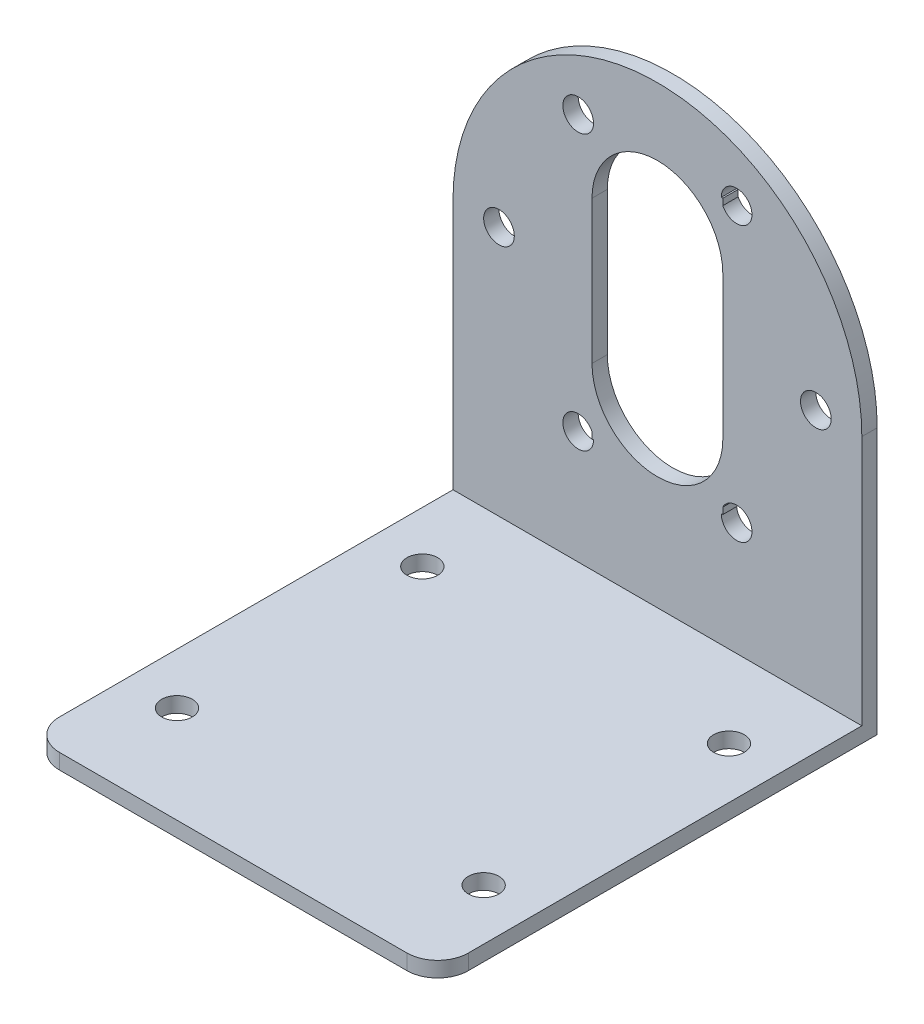
SolidWorks part; units mm, degrees
ref_plane "Alzado" through (0, 0, 0) normal (0, 0, 1) x (1, 0, 0)
ref_plane "Planta" through (0, 0, 0) normal (0, 1, 0) x (1, 0, 0)
ref_plane "Vista lateral" through (0, 0, 0) normal (1, 0, 0) x (0, 0, -1)
sketch "Croquis1" plane through (0, 0, 0) normal (0, 0, 1) x (1, 0, 0)
  line L1 (0, 0) -> (40, 0)
  line L2 (0, 0) -> (0, 26)
  line L4 (40, 0) -> (40, 26)
  arc A0 (40, 26) -> (0, 26) centre (20, 26) ccw
  dimension "D3" = 40
  dimension "D5" = 20
  dimension "D1" = 40
extrude "Saliente-Extruir1" add sketch "Croquis1" along normal blind 1.5
sketch "Croquis2" plane through (0, 0, 1.5) normal (0, 0, 1) x (1, 0, 0)
  line L0 (40, 0) -> (40, 26) construction
  line L1 (0, 0) -> (40, 0)
  line L2 (0, 0) -> (0, 1.5)
  line L3 (0, 1.5) -> (40, 1.5)
  line L4 (40, 0) -> (40, 1.5)
  dimension "D1" = 1.5
extrude "Saliente-Extruir2" add sketch "Croquis2" along normal blind 41.5
sketch "Croquis3" plane through (0, 1.5, 0) normal (0, 1, 0) x (1, 0, 0)
  line L0 (0, -43) -> (0, -1.5) construction
  line L1 (40, -43) -> (0, -43) construction
  circle A0 centre (5, -33.5) radius 1.5
  circle A1 centre (5, -9.5) radius 1.5
  circle A2 centre (35, -9.5) radius 1.5
  circle A3 centre (35, -33.5) radius 1.5
  dimension "D3" = 3
  dimension "D4" = 3
  dimension "D8" = 30
  dimension "D1" = 5
  dimension "D2" = 9.5
  dimension "D5" = 5
  dimension "D6" = 24
  dimension "D7" = 30
  dimension "D9" = 9.5
  dimension "D10" = 24
extrude "Cortar-Extruir1" cut sketch "Croquis3" against normal blind 41.5
sketch "Croquis4" plane through (0, 0, 1.5) normal (0, 0, 1) x (1, 0, 0)
  line L0 (20, 26) -> (24.305, 26) construction
  line L1 (13.6, 33) -> (13.6, 19)
  line L2 (13.6, 39.4) -> (13.7498, 39.4)
  line L3 (13.6, 39.4) -> (13.6, 38.7696)
  line L4 (13.6, 12.6) -> (13.7498, 12.6)
  line L5 (26.4, 39.4) -> (26.4, 38.7696)
  line L6 (26.2502, 39.4) -> (26.4, 39.4)
  line L7 (26.4, 33) -> (26.4, 19)
  line L8 (26.2502, 12.6) -> (26.4, 12.6)
  line L9 (13.6, 13.2304) -> (13.6, 12.6)
  line L10 (26.4, 13.2304) -> (26.4, 12.6)
  circle A0 centre (20, 26) radius 15.5 construction
  circle A1 centre (4.5, 26) radius 1.5
  circle A2 centre (12.25, 39.4234) radius 1.5
  circle A3 centre (27.75, 39.4234) radius 1.5
  circle A4 centre (35.5, 26) radius 1.5
  circle A5 centre (27.75, 12.5766) radius 1.5
  circle A6 centre (12.25, 12.5766) radius 1.5
  arc A7 (26.4, 33) -> (13.6, 33) centre (20, 33) ccw
  arc A8 (26.4, 19) -> (13.6, 19) centre (20, 19) cw
  point P17 (20, 26)
  dimension "D1" = 31
  dimension "D2" = 3
  dimension "D3" = 26.8
  dimension "D7" = 12.8
  dimension "D4" = 12.8
  dimension "D5" = 13.4
  dimension "D6" = 6.4
  dimension "D8" = 6.4
  dimension "D9" = 6.4
extrude "Cortar-Extruir2" cut sketch "Croquis4" against normal blind 41.5 contours A1 | L9 A6 L4 | A8 L7 A7 L1 | L5 A3 L6 | L8 A5 L10 | A2 | A4
fillet "Fillet1" radius 3 2 edges at (40, 0.75, 43) (0, 0.75, 43)
